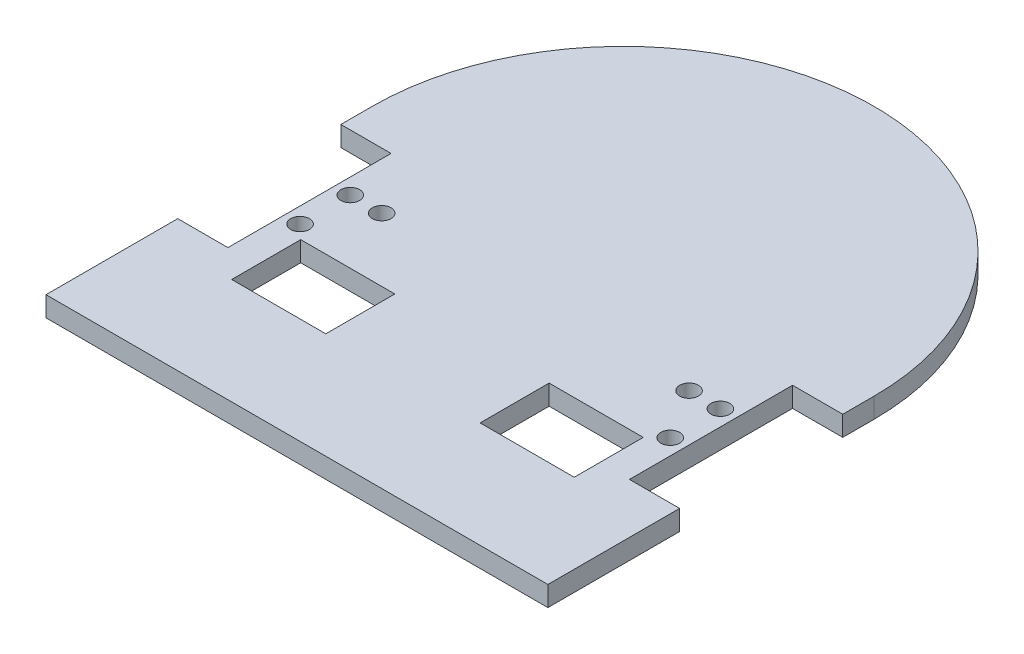
SolidWorks part; units mm, degrees
ref_plane "Front Plane" through (0, 0, 0) normal (0, 0, 1) x (1, 0, 0)
ref_plane "Top Plane" through (0, 0, 0) normal (0, 1, 0) x (1, 0, 0)
ref_plane "Right Plane" through (0, 0, 0) normal (1, 0, 0) x (0, 0, -1)
sketch "Sketch1" plane through (0, 0, 0) normal (0, 1, 0) x (1, 0, 0)
  line L0 (-20, 0) -> (-20, -26)
  line L1 (-20, -26) -> (20, -26)
  line L2 (20, 0) -> (20, -26)
  line L3 (20, -26) -> (20, 0)
  line L5 (-20, 0) -> (-20, -26)
  arc A0 (20, 0) -> (-20, 0) centre (0, 0) ccw
  dimension "D1" = 40
  dimension "D2" = 0
  dimension "D3" = 0
  dimension "D4" = 26
extrude "Boss-Extrude1" add sketch "Sketch1" along normal blind 1.6 contours L3 A0 L5 L1
sketch "Sketch2" plane through (0, 3, 0) normal (0, 1, 0) x (1, 0, 0)
  line L0 (0, -20) -> (0, 0.4984)
  line L1 (-20, -20) -> (20, -20) construction
  line L3 (20, -20) -> (20, 0) construction
  line L4 (20, -2.5) -> (16, -2.5)
  line L5 (16, -2.5) -> (16, -15.5)
  line L6 (16, -15.5) -> (20, -15.5)
  line L8 (-16, -15.5) -> (-20, -15.5)
  line L9 (-16, -2.5) -> (-16, -15.5)
  line L10 (-20, -2.5) -> (-16, -2.5)
  line L11 (20, -15.5) -> (20, -2.5)
  line L12 (-20, -15.5) -> (-20, -2.5)
  dimension "D3" = 16
extrude "Cut-Extrude2" cut sketch "Sketch2" against normal blind 10
sketch "Sketch3" plane through (0, 1.6, 0) normal (0, 1, 0) x (1, 0, 0)
  line L0 (-16, -9) -> (14.5835, -9) construction
  line L1 (-13.65, -12.05) -> (-6.15, -12.05)
  line L2 (-13.65, -12.05) -> (-13.65, -17.55)
  line L3 (-13.65, -17.55) -> (-6.15, -17.55)
  line L4 (-6.15, -12.05) -> (-6.15, -17.55)
  line L9 (-16, -2.5) -> (-16, -15.5) construction
  line L10 (0, 21.5474) -> (0, -24.0588) construction
  dimension "D1" = 3.05
  dimension "D2" = 7.5
  dimension "D3" = 5.5
  dimension "D4" = 2.35
extrude "Cut-Extrude3" cut sketch "Sketch3" against normal blind 10 contours L2 L1 L4 L3
mirror "Mirror1" about plane through (0, 0, 0) normal (1, 0, 0) of "Cut-Extrude3"
sketch "Sketch4" plane through (0, 1.6, 0) normal (0, 1, 0) x (1, 0, 0)
  line L0 (-16, -9) -> (16, -9) construction
  line L1 (-16, -2.5) -> (-16, -15.5) construction
  line L2 (16, -2.5) -> (16, -15.5) construction
  circle A0 centre (-14.75, -7) radius 0.75
  circle A1 centre (-14.75, -11) radius 0.75
  circle A2 centre (-12.25, -7) radius 0.75
  dimension "D2" = 1.5
  dimension "D1" = 1.25
  dimension "D3" = 2
  dimension "D4" = 2
  dimension "D5" = 2.5
extrude "Cut-Extrude4" cut sketch "Sketch4" against normal blind 10 contours A0 | A2 | A1
mirror "Mirror2" about plane through (0, 0, 0) normal (1, 0, 0) of "Cut-Extrude4"
